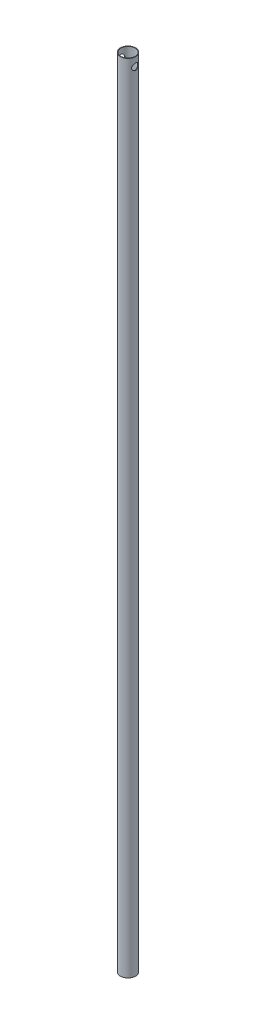
SolidWorks part; units mm, degrees
ref_plane "Front Plane" through (0, 0, 0) normal (0, 0, 1) x (1, 0, 0)
ref_plane "Top Plane" through (0, 0, 0) normal (0, 1, 0) x (1, 0, 0)
ref_plane "Right Plane" through (0, 0, 0) normal (1, 0, 0) x (0, 0, -1)
sketch "Sketch1" plane through (0, 0, 0) normal (0, 1, 0) x (1, 0, 0)
  circle A0 centre (0, 0) radius 17.46
  circle A1 centre (0, 0) radius 16.46
  dimension "D1" = 34.92
  dimension "D2" = 32.92
extrude "Boss-Extrude1" add sketch "Sketch1" along normal blind 1828.8
sketch "Sketch2" plane through (0, 0, 0) normal (1, 0, 0) x (0, 0, -1)
  line L0 (0, 1828.8) -> (0, 1788.8) construction
  line L1 (17.46, 1828.8) -> (-17.46, 1828.8) construction
  line L2 (16.46, 914.4) -> (-17.46, 914.4) construction
  line L3 (16.46, 0) -> (16.46, 1828.8) construction
  line L4 (-17.46, 1828.8) -> (-17.46, 0) construction
  circle A0 centre (0, 1808.8) radius 7.5
  dimension "D2" = 15
  dimension "D1" = 40
extrude "Cut-Extrude1" cut sketch "Sketch2" against normal through all both and the other way through all
sketch "Sketch3" plane through (0, 0, 0) normal (0, 0, 1) x (1, 0, 0)
  point P0 (0, 900.6858)
